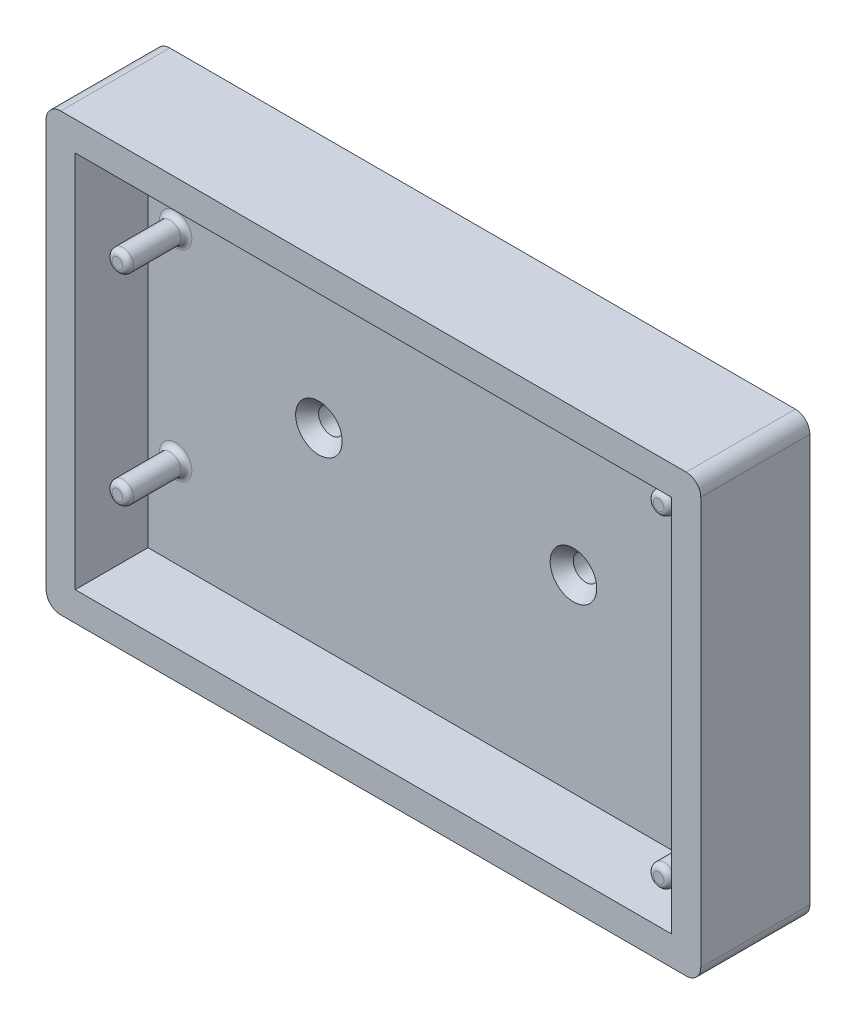
SolidWorks part; units mm, degrees
ref_plane "Plan de face" through (0, 0, 0) normal (0, 0, 1) x (1, 0, 0)
ref_plane "Plan de dessus" through (0, 0, 0) normal (0, 1, 0) x (1, 0, 0)
ref_plane "Plan de droite" through (0, 0, 0) normal (1, 0, 0) x (0, 0, -1)
sketch "Esquisse1" plane through (0, 0, 0) normal (0, 0, 1) x (1, 0, 0)
  line L1 (-45, 30) -> (45, 30)
  line L2 (-45, 30) -> (-45, -30)
  line L3 (-45, -30) -> (45, -30)
  line L4 (45, 30) -> (45, -30)
  line L5 (-45, 30) -> (45, -30) construction
  line L6 (-45, -30) -> (45, 30) construction
  point P0 (0, 0)
  dimension "D1" = 90
  dimension "D2" = 60
extrude "Boss.-Extru.1" add sketch "Esquisse1" along normal blind 5 contours L2 L3 L4 L1
sketch "Esquisse2" plane through (0, 0, 5) normal (0, 0, 1) x (1, 0, 0)
  line L0 (-45, 30) -> (45, 30) construction
  line L1 (-41, 26) -> (41, 26)
  line L2 (-41, 26) -> (-41, -26)
  line L3 (-41, -26) -> (41, -26)
  line L4 (41, 26) -> (41, -26)
  line L5 (-41, 26) -> (41, -26) construction
  line L6 (-41, -26) -> (41, 26) construction
  line L7 (-45, 30) -> (-45, -30) construction
  line L9 (-45, 30) -> (45, 30)
  line L10 (-45, 30) -> (-45, -30)
  line L11 (-45, -30) -> (45, -30)
  line L12 (45, 30) -> (45, -30)
  line L13 (-45, 30) -> (45, -30) construction
  line L14 (-45, -30) -> (45, 30) construction
  point P0 (0, 0)
  point P10 (0, 0)
  dimension "D1" = 4
  dimension "D2" = 4
extrude "Boss.-Extru.2" add sketch "Esquisse2" along normal blind 10
sketch "Esquisse3" plane through (0, 0, 5) normal (0, 0, 1) x (1, 0, 0)
  circle A0 centre (-37.2, 13.8) radius 1.475
  circle A1 centre (-37.2, -13.8) radius 1.475
  circle A2 centre (37.2, -22.2) radius 1.475
  circle A3 centre (37.2, 22.2) radius 1.475
  dimension "D1" = 2.95
extrude "Boss.-Extru.3" add sketch "Esquisse3" along normal blind 8
hole_wizard "Fraisage pour vis à tête fraisée bombée #51" positions "Esquisse5" profile "Esquisse7" countersink size "#5" standard "Ansi Inch" end condition through all
sketch "Esquisse5" plane through (0, 0, 5) normal (0, 0, 1) x (1, 0, 0)
  line L0 (-17.5, 0) -> (17.5, 0) construction
  point P0 (-17.5, 0)
  point P2 (17.5, 0)
  point P10 (0, 0)
  dimension "D1" = 35
sketch "Esquisse7" plane through (-17.5, 0, 5) normal (1, 0, 0) x (0, -1, 0)
  line L0 (0, 0) -> (0, 5)
  line L1 (0, 5) -> (1.7272, 5)
  line L2 (1.7272, 5) -> (1.7272, 1.6947)
  line L3 (1.7272, 1.6947) -> (3.2004, 0)
  line L5 (3.2004, 0) -> (0, 0)
  line L6 (-1.7272, 1.6947) -> (-3.2004, 0) construction
  line L11 (0, -6.35) -> (0, 107.95) construction
  dimension "Diamètre du perçage jusqu'au prochain" = 3.4544
  dimension "Profondeur du perçage jusqu'au prochain" = 5
  dimension "Diamètre du fraisage entrant" = 6.4008
  dimension "Angle du fraisage entrant" = 82
fillet "Congé1" radius 2 4 edges at (-45, -30, 7.5) (-45, 30, 7.5) (45, 30, 7.5) (45, -30, 7.5)
fillet "Congé2" radius 0.75 8 edges at (38.675, 22.2, 13) (-35.725, 13.8, 13) (35.725, 22.2, 5) (-38.675, 13.8, 5) (-38.675, -13.8, 5) (35.725, -22.2, 5) (-35.725, -13.8, 13) (38.675, -22.2, 13)
